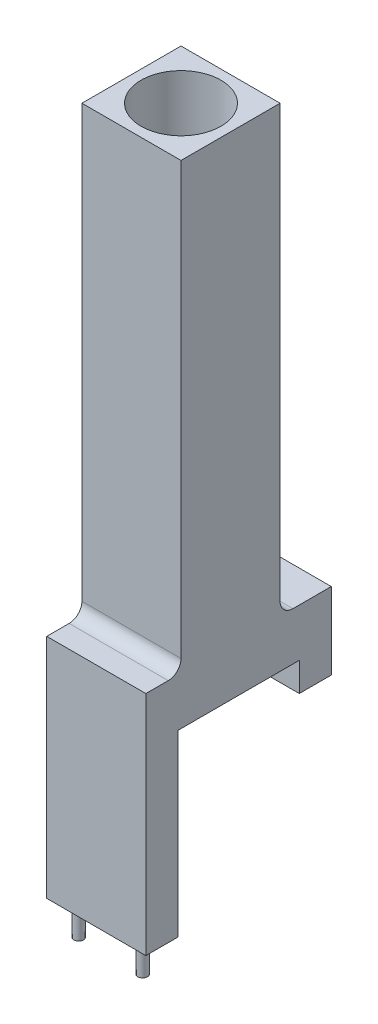
SolidWorks part; units mm, degrees
ref_plane "Front Plane" through (0, 0, 0) normal (0, 0, 1) x (1, 0, 0)
ref_plane "Top Plane" through (0, 0, 0) normal (0, 1, 0) x (1, 0, 0)
ref_plane "Right Plane" through (0, 0, 0) normal (1, 0, 0) x (0, 0, -1)
sketch "Sketch1" plane through (0, 0, 0) normal (0, 0, 1) x (1, 0, 0)
  line L0 (-15.5, 182.5) -> (-15.5, 28.5657)
  line L1 (15.5, 28.5657) -> (15.5, 182.5)
  line L2 (15.5, 182.5) -> (-15.5, 182.5)
  arc A0 (15.5, 28.5657) -> (-15.5, 28.5657) centre (0, 0) ccw
  dimension "D1" = 65
  dimension "D2" = 31
  dimension "D3" = 182.5
extrude "Boss-Extrude1" add sketch "Sketch1" along normal blind 31
sketch "Sketch3" plane through (0, 182.5, 0) normal (0, 1, 0) x (1, 0, 0)
  circle A0 centre (0, -15.5) radius 12.5
  dimension "D1" = 25
  dimension "D2" = 15.5
extrude "Cut-Extrude1" cut sketch "Sketch3" against normal through all
sketch "Sketch4" plane through (0, 0, 31) normal (0, 0, 1) x (1, 0, 0)
  line L0 (-15.5, 182.5) -> (-15.5, 28.5657) construction
  line L1 (-15.5, 43.5657) -> (15.5, 43.5657)
  line L2 (-15.5, 43.5657) -> (-15.5, 28.5657)
  line L3 (-15.5, 28.5657) -> (15.5, 28.5657)
  line L4 (15.5, 43.5657) -> (15.5, 28.5657)
  line L5 (15.5, 28.5657) -> (15.5, 182.5) construction
  point P8 (0, 0)
  point P10 (0, 0)
  dimension "D2" = 15
extrude "Boss-Extrude2" add sketch "Sketch4" along normal blind 11
sketch "Sketch5" plane through (0, 28.5657, 0) normal (0, -1, 0) x (1, 0, 0)
  line L0 (15.5, 42) -> (15.5, 31) construction
  line L1 (-15.5, 42) -> (15.5, 42)
  line L2 (-15.5, 42) -> (-15.5, 32)
  line L3 (-15.5, 32) -> (15.5, 32)
  line L4 (15.5, 42) -> (15.5, 32)
  dimension "D1" = 10
extrude "Boss-Extrude3" add sketch "Sketch5" along normal blind 56
sketch "Sketch6" plane through (0, -27.4343, 0) normal (0, -1, 0) x (1, 0, 0)
  line L0 (15.5, 42) -> (-15.5, 42) construction
  line L1 (0, 42) -> (0, 32) construction
  line L2 (-15.5, 32) -> (15.5, 32) construction
  circle A0 centre (-10, 37.5) radius 1.5
  circle A1 centre (10, 37.5) radius 1.5
  point P10 (0, 0)
  dimension "D2" = 3
  dimension "D1" = 4.5
  dimension "D3" = 10
extrude "Boss-Extrude4" add sketch "Sketch6" along normal blind 10
sketch "Sketch7" plane through (0, 0, 0) normal (0, 0, -1) x (-1, 0, 0)
  line L0 (15.5, 182.5) -> (15.5, 28.5657) construction
  line L1 (-15.5, 28.5657) -> (15.5, 28.5657)
  line L2 (-15.5, 28.5657) -> (-15.5, 43.5657)
  line L3 (-15.5, 43.5657) -> (15.5, 43.5657)
  line L4 (15.5, 28.5657) -> (15.5, 43.5657)
  dimension "D1" = 15
extrude "Boss-Extrude5" add sketch "Sketch7" along normal blind 16
sketch "Sketch8" plane through (0, 28.5657, 0) normal (0, -1, 0) x (1, 0, 0)
  line L0 (15.5, -16) -> (15.5, 0) construction
  line L1 (-15.5, -16) -> (15.5, -16)
  line L2 (-15.5, -16) -> (-15.5, -6)
  line L3 (-15.5, -6) -> (15.5, -6)
  line L4 (15.5, -16) -> (15.5, -6)
  dimension "D1" = 10
extrude "Boss-Extrude6" add sketch "Sketch8" along normal blind 9
fillet "Fillet1" radius 4 2 edges at (0, 43.5657, 31) (0, 43.5657, 0)
